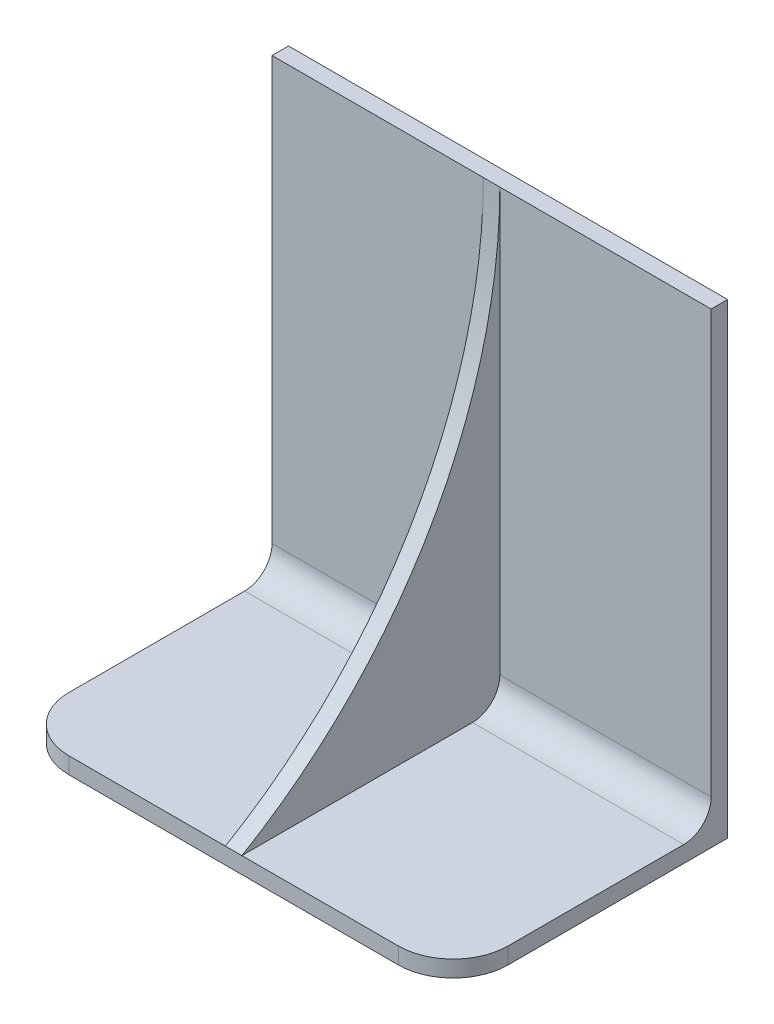
SolidWorks part; units mm, degrees
ref_plane "前基準面" through (0, 0, 0) normal (0, 0, 1) x (1, 0, 0)
ref_plane "上基準面" through (0, 0, 0) normal (0, 1, 0) x (1, 0, 0)
ref_plane "右基準面" through (0, 0, 0) normal (1, 0, 0) x (0, 0, -1)
sketch "Sketch1" plane through (0, 0, 0) normal (0, 1, 0) x (1, 0, 0)
  line L1 (-40, -25) -> (40, -25)
  line L2 (-40, -25) -> (-40, 25)
  line L3 (-40, 25) -> (40, 25)
  line L4 (40, -25) -> (40, 25)
  line L5 (0, 25) -> (0, -25) construction
  line L6 (-40, 0) -> (40, 0) construction
  point P0 (0, 0)
  dimension "D1" = 50
  dimension "D2" = 80
extrude "Boss-Extrude1" add sketch "Sketch1" along normal blind 3
sketch "Sketch2" plane through (0, 3, 0) normal (0, 1, 0) x (1, 0, 0)
  line L0 (40, -25) -> (40, 25) construction
  line L1 (-40, 25) -> (40, 25)
  line L2 (-40, 25) -> (-40, 22)
  line L3 (-40, 22) -> (40, 22)
  line L4 (40, 25) -> (40, 22)
  dimension "D1" = 3
extrude "Boss-Extrude2" add sketch "Sketch2" along normal blind 82
sketch "Sketch3" plane through (0, 0, 0) normal (1, 0, 0) x (0, 0, -1)
  line L0 (22, 85) -> (22, 3) construction
  line L1 (-25, 3) -> (22, 3) construction
  line L2 (22, 85) -> (22, 3)
  line L3 (-25, 3) -> (22, 3)
  arc A0 (22, 85) -> (-25, 3) centre (-73.0319, 85) cw
extrude "Boss-Extrude3" add sketch "Sketch3" along normal mid plane 3
fillet "Fillet1" radius 10 2 edges at (-40, 1.5, 25) (40, 1.5, 25)
fillet "Fillet2" radius 5 2 edges at (20.75, 3, -22) (-20.75, 3, -22)
